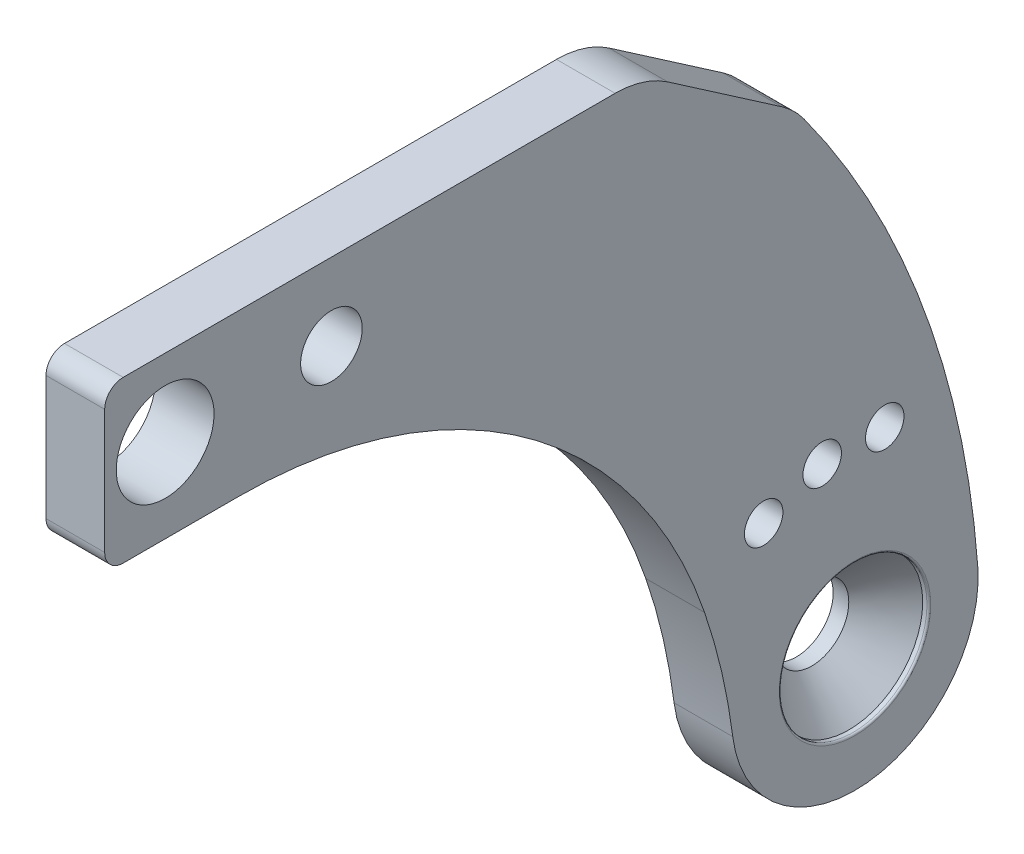
SolidWorks part; units mm, degrees
material "AISI 1020"
ref_plane "Alzado" through (0, 0, 0) normal (0, 0, 1) x (1, 0, 0)
ref_plane "Planta" through (0, 0, 0) normal (0, 1, 0) x (1, 0, 0)
ref_plane "Vista lateral" through (0, 0, 0) normal (1, 0, 0) x (0, 0, -1)
sketch "Croquis13" plane through (0, 0, 0) normal (1, 0, 0) x (0, 0, -1)
  line L3 (102.1634, -4.3272) -> (81.5744, 9.8534)
  line L4 (73.066, 12.5) -> (-16.8165, 12.5)
  line L5 (-21.8165, 7.5) -> (-21.8165, -8.6261)
  line L6 (-16.8165, -13.6261) -> (43.1835, -13.6261)
  line L11 (112, -85) -> (132.2446, -66.7477) construction
  circle A0 centre (27, 0) radius 5
  circle A1 centre (0, 0) radius 5
  arc A5 (81.5744, 9.8534) -> (73.066, 12.5) centre (73.066, -2.5) ccw
  arc A6 (-16.8165, 12.5) -> (-21.8165, 7.5) centre (-16.8165, 7.5) ccw
  arc A7 (-21.8165, -8.6261) -> (-16.8165, -13.6261) centre (-16.8165, -8.6261) ccw
  circle A13 centre (112, -85) radius 6
  arc A15 (43.1835, -13.6261) -> (92.1589, -87.5159) centre (-7.0468, -100.0953) cw
  arc A16 (131.9456, -83.5261) -> (102.1634, -4.3272) centre (-17.6465, -94.5801) ccw
  arc A17 (92.1589, -87.5159) -> (131.9456, -83.5261) centre (112, -85) ccw
  dimension "D1" = 10
  dimension "D2" = 10
  dimension "D3" = 27
  dimension "D6" = 5
  dimension "D10" = 5
  dimension "D12" = 150
  dimension "D16" = 15
  dimension "D22" = 40
  dimension "D23" = 12
  dimension "D24" = 85
  dimension "D15" = 100
  dimension "D14" = 112
  dimension "D4" = 21.8165
  dimension "D5" = 26.1261
  dimension "D7" = 5
  dimension "D8" = 5
  dimension "D9" = 13.6261
  dimension "D11" = 16.1261
  dimension "D13" = 60
  dimension "D17" = 25
  dimension "D18" = 89.8824
  dimension "D19" = 8.5084
  dimension "D20" = 2.6466
  dimension "D21" = 145.443
extrude "Saliente-Extruir1" add sketch "Croquis13" along normal mid plane 9.53
ref_plane "Plano1" through (0, -85, 0) normal (0, 1, 0) x (1, 0, 0)
sketch "Croquis15" plane through (0, -85, 0) normal (0, 1, 0) x (1, 0, 0)
  line L0 (4.765, 112) -> (-4.765, 112) construction
  line L1 (4.765, 106) -> (4.765, 118) construction
  line L2 (-4.765, 118) -> (-4.765, 106) construction
  line L3 (4.765, 106.01) -> (4.765, 100)
  line L4 (4.765, 92.1589) -> (4.765, 132) construction
  line L5 (3.765, 100) -> (-2.245, 106.01)
  line L6 (-2.245, 106.01) -> (4.765, 106.01)
  line L7 (4.765, 100) -> (3.765, 100)
  dimension "D2" = 12
  dimension "D1" = 112
  dimension "D3" = 5.99
  dimension "D4" = 1
  dimension "D5" = 135
revolve "Cortar-Revolución2" cut sketch "Croquis15" angle 360 about L0
fillet "Redondeo2" radius 0.3 1 edges at (4.765, -85, -124)
fillet "Redondeo3" radius 80 1 edges at (0, -13.6261, -43.1835)
fillet "Redondeo4" radius 15 1 edges at (0, -4.3272, -102.1634)
sketch "Croquis18" plane through (-4.765, 0, 0) normal (-1, 0, 0) x (0, 0, 1)
  line L0 (-97.1752, -60) -> (-116.8375, -56.3404) construction
  line L1 (-107.0064, -58.1702) -> (-106.6817, -56.4257) construction
  circle A0 centre (-112, -85) radius 6 construction
  circle A1 centre (-112, -85) radius 6 construction
  circle A2 centre (-112, -85) radius 29.065 construction
  circle A3 centre (-97.1752, -60) radius 3.125
  circle A4 centre (-116.8375, -56.3404) radius 3.125
  circle A5 centre (-106.6817, -56.4257) radius 3.125
  dimension "D1" = 58.13
  dimension "D2" = 6.25
  dimension "D3" = 6.25
  dimension "D4" = 20
  dimension "D5" = 25
  dimension "D6" = 6.25
extrude "Cortar-Extruir2" cut sketch "Croquis18" against normal up to next
sketch "Croquis19" plane through (-4.765, 0, 0) normal (-1, 0, 0) x (0, 0, 1)
  line L7 (-94.2885, -55) -> (-100.062, -55) construction
  line L8 (-100.062, -55) -> (-102.9487, -60) construction
  line L9 (-102.9487, -60) -> (-100.062, -65) construction
  line L10 (-100.062, -65) -> (-94.2885, -65) construction
  line L11 (-94.2885, -65) -> (-91.4017, -60) construction
  line L12 (-91.4017, -60) -> (-94.2885, -55) construction
  line L13 (-113.9508, -51.3404) -> (-119.7243, -51.3404) construction
  line L14 (-119.7243, -51.3404) -> (-122.6111, -56.3404) construction
  line L15 (-122.6111, -56.3404) -> (-119.7243, -61.3404) construction
  line L16 (-119.7243, -61.3404) -> (-113.9508, -61.3404) construction
  line L17 (-113.9508, -61.3404) -> (-111.064, -56.3404) construction
  line L18 (-111.064, -56.3404) -> (-113.9508, -51.3404) construction
  circle A0 centre (-116.8375, -56.3404) radius 3.125 construction
  circle A1 centre (-97.1752, -60) radius 3.125 construction
  circle A2 centre (-116.8375, -56.3404) radius 3.125 construction
  circle A3 centre (-97.1752, -60) radius 3.125 construction
  circle A4 centre (-97.1752, -60) radius 5.7735 construction
  circle A5 centre (-116.8375, -56.3404) radius 5.7735 construction
  dimension "D1" = 10
  dimension "D2" = 10
sketch "Croquis20" plane through (0, 0, 0) normal (1, 0, 0) x (0, 0, -1)
  line L0 (-21.8165, 7.5) -> (-21.8165, -8.6261) construction
  line L1 (-21.8165, 7.5) -> (-21.8165, -8.6261)
  line L2 (-16.8165, 12.5) -> (-9.8165, 12.5)
  line L3 (73.066, 12.5) -> (-16.8165, 12.5) construction
  line L4 (-9.8165, 12.5) -> (-9.8165, -13.6261)
  line L5 (-16.8165, -13.6261) -> (11.8781, -13.6261) construction
  line L6 (-9.8165, -13.6261) -> (-16.8165, -13.6261)
  arc A0 (-21.8165, -8.6261) -> (-16.8165, -13.6261) centre (-16.8165, -8.6261) ccw construction
  arc A1 (-16.8165, 12.5) -> (-21.8165, 7.5) centre (-16.8165, 7.5) ccw construction
  arc A2 (-21.8165, -8.6261) -> (-16.8165, -13.6261) centre (-16.8165, -8.6261) ccw
  arc A3 (-16.8165, 12.5) -> (-21.8165, 7.5) centre (-16.8165, 7.5) ccw
  dimension "D1" = 12
extrude "Cortar-Extruir3" cut sketch "Croquis20" against normal through all both and the other way through all
fillet "Redondeo5" radius 3 2 edges at (0, -13.6261, 9.8165) (0, 12.5, 9.8165)
sketch "Croquis21" plane through (0, 0, 0) normal (1, 0, 0) x (0, 0, -1)
  circle A0 centre (0, 0) radius 7.94
  dimension "D1" = 15.88
extrude "Cortar-Extruir4" cut sketch "Croquis21" against normal through all both and the other way through all
